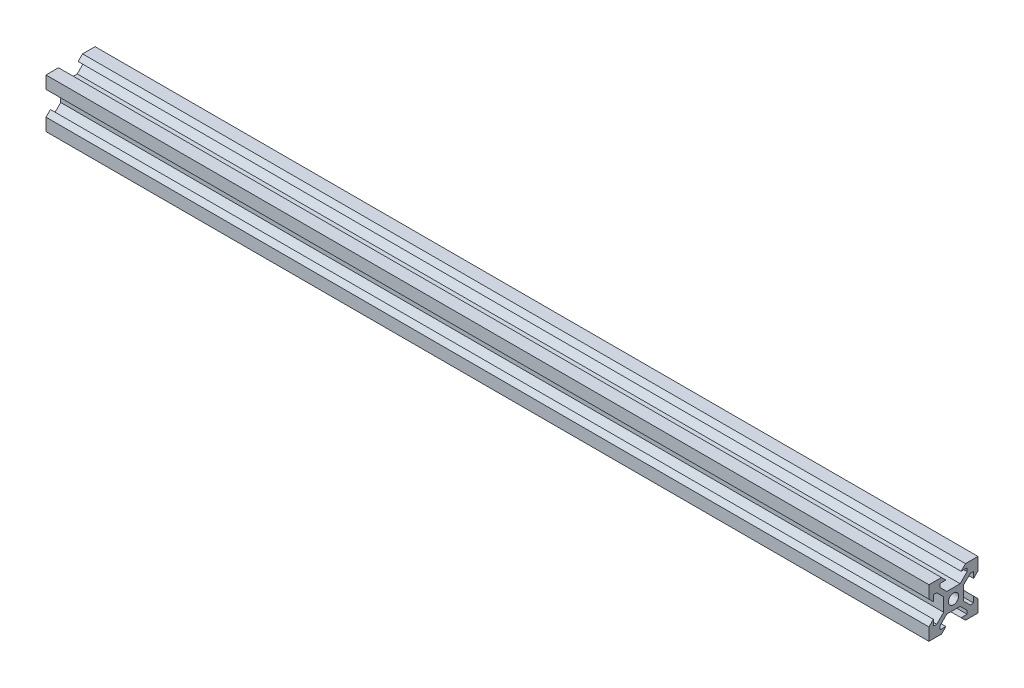
SolidWorks part; units mm, degrees
ref_plane "Front Plane" through (0, 0, 0) normal (0, 0, 1) x (1, 0, 0)
ref_plane "Top Plane" through (0, 0, 0) normal (0, 1, 0) x (1, 0, 0)
ref_plane "Right Plane" through (0, 0, 0) normal (1, 0, 0) x (0, 0, -1)
sketch "Sketch1" plane through (0, 0, 0) normal (1, 0, 0) x (0, 0, -1)
  line L0 (0, 0) -> (0, 20) construction
  line L1 (10, 14) -> (10, 6) construction
  line L2 (5.1, 20) -> (5.1, 0) construction
  line L3 (6.9, 18.2) -> (6.9, 1.8) construction
  line L4 (4.4444, 18.2) -> (4.4444, 1.8) construction
  line L5 (3.1716, 15.5556) -> (3.1716, 4.4444) construction
  line L6 (10, 6) -> (10, 14) construction
  line L7 (6, 12.7272) -> (6, 7.2728)
  line L8 (6, 7.2728) -> (3.1716, 4.4444)
  line L9 (1.8, 4.4444) -> (3.1716, 4.4444)
  line L10 (1.8, 4.4444) -> (1.8, 6.9)
  line L11 (1.8, 6.9) -> (0, 5.1)
  line L12 (0, 5.1) -> (0, 0)
  line L13 (0, 0) -> (5.1, 0)
  line L14 (5.1, 0) -> (6.9, 1.8)
  line L15 (6.9, 1.8) -> (4.4444, 1.8)
  line L16 (4.4444, 3.1716) -> (4.4444, 1.8)
  line L17 (4.4444, 3.1716) -> (7.2728, 6)
  line L18 (7.2728, 6) -> (12.7272, 6)
  line L19 (1.8, 15.5556) -> (1.8, 4.4444) construction
  line L20 (20, 10) -> (0, 10) construction
  line L21 (1.8, 10) -> (0, 10) construction
  line L22 (7.2728, 14) -> (7.2728, 6) construction
  line L23 (6.9, 1.8) -> (0, 1.8) construction
  line L24 (5.8586, 15.4142) -> (5.8586, 4.5858) construction
  line L25 (4.5858, 14.1414) -> (4.5858, 5.8586) construction
  line L26 (10, 10) -> (20, 20) construction
  line L27 (14.1414, 15.4142) -> (15.4142, 14.1414) construction
  line L28 (10, 10) -> (0, 0) construction
  line L29 (14.7778, 14.7778) -> (20, 20) construction
  line L30 (5.8586, 4.5858) -> (4.5858, 5.8586) construction
  line L31 (5.2222, 5.2222) -> (0, 0) construction
  line L32 (14.7778, 5.2222) -> (20, 0) construction
  line L33 (10, 6) -> (10, 14) construction
  line L34 (14.1414, 4.5858) -> (15.4142, 5.8586) construction
  line L35 (10, 10) -> (20, 0) construction
  line L36 (15.4142, 14.1414) -> (15.4142, 5.8586) construction
  line L37 (14.1414, 15.4142) -> (14.1414, 4.5858) construction
  line L38 (13.1, 1.8) -> (20, 1.8) construction
  line L39 (12.7272, 14) -> (12.7272, 6) construction
  line L40 (18.2, 10) -> (20, 10) construction
  line L41 (18.2, 15.5556) -> (18.2, 4.4444) construction
  line L42 (16.8284, 15.5556) -> (16.8284, 4.4444) construction
  line L43 (15.5556, 18.2) -> (15.5556, 1.8) construction
  line L44 (13.1, 18.2) -> (13.1, 1.8) construction
  line L45 (14.9, 20) -> (14.9, 0) construction
  line L46 (20, 0) -> (20, 20) construction
  line L47 (14, 12.7272) -> (16.8284, 15.5556)
  line L48 (18.2, 15.5556) -> (16.8284, 15.5556)
  line L49 (18.2, 15.5556) -> (18.2, 13.1)
  line L50 (18.2, 13.1) -> (20, 14.9)
  line L51 (20, 14.9) -> (20, 20)
  line L52 (20, 20) -> (14.9, 20)
  line L53 (14.9, 20) -> (13.1, 18.2)
  line L54 (13.1, 18.2) -> (15.5556, 18.2)
  line L55 (15.5556, 16.8284) -> (15.5556, 18.2)
  line L56 (15.5556, 16.8284) -> (12.7272, 14)
  line L57 (15.5556, 3.1716) -> (12.7272, 6)
  line L58 (15.5556, 3.1716) -> (15.5556, 1.8)
  line L59 (13.1, 1.8) -> (15.5556, 1.8)
  line L60 (14.9, 0) -> (13.1, 1.8)
  line L61 (20, 0) -> (14.9, 0)
  line L62 (20, 5.1) -> (20, 0)
  line L63 (5.2222, 14.7778) -> (0, 20) construction
  line L64 (5.8586, 15.4142) -> (4.5858, 14.1414) construction
  line L65 (18.2, 6.9) -> (20, 5.1)
  line L66 (10, 10) -> (0, 20) construction
  line L67 (18.2, 4.4444) -> (18.2, 6.9)
  line L68 (18.2, 4.4444) -> (16.8284, 4.4444)
  line L69 (14, 7.2728) -> (16.8284, 4.4444)
  line L70 (14, 12.7272) -> (14, 7.2728)
  line L93 (7.2728, 14) -> (12.7272, 14)
  line L94 (4.4444, 16.8284) -> (7.2728, 14)
  line L95 (4.4444, 16.8284) -> (4.4444, 18.2)
  line L96 (6.9, 18.2) -> (4.4444, 18.2)
  line L97 (5.1, 20) -> (6.9, 18.2)
  line L98 (0, 20) -> (5.1, 20)
  line L99 (0, 14.9) -> (0, 20)
  line L100 (1.8, 13.1) -> (0, 14.9)
  line L101 (1.8, 15.5556) -> (1.8, 13.1)
  line L102 (1.8, 15.5556) -> (3.1716, 15.5556)
  line L103 (6, 12.7272) -> (3.1716, 15.5556)
  circle A0 centre (10, 10) radius 2.1
  point P57 (14, 10)
  point P108 (6, 10)
  dimension "D5" = 4.2
  dimension "D2" = 20
  dimension "D3" = 10
  dimension "D4" = 5.1
  dimension "D6" = 10
  dimension "D7" = 1.8
  dimension "D8" = 1.8
  dimension "D9" = 1.3716
  dimension "D10" = 1.8
  dimension "D11" = 1.8
  dimension "D12" = 4
  dimension "D13" = 1.2728
  dimension "D14" = 5.1
  dimension "D16" = 1.8
  dimension "D18" = 4
extrude "Boss-Extrude1" add sketch "Sketch1" along normal blind 360
